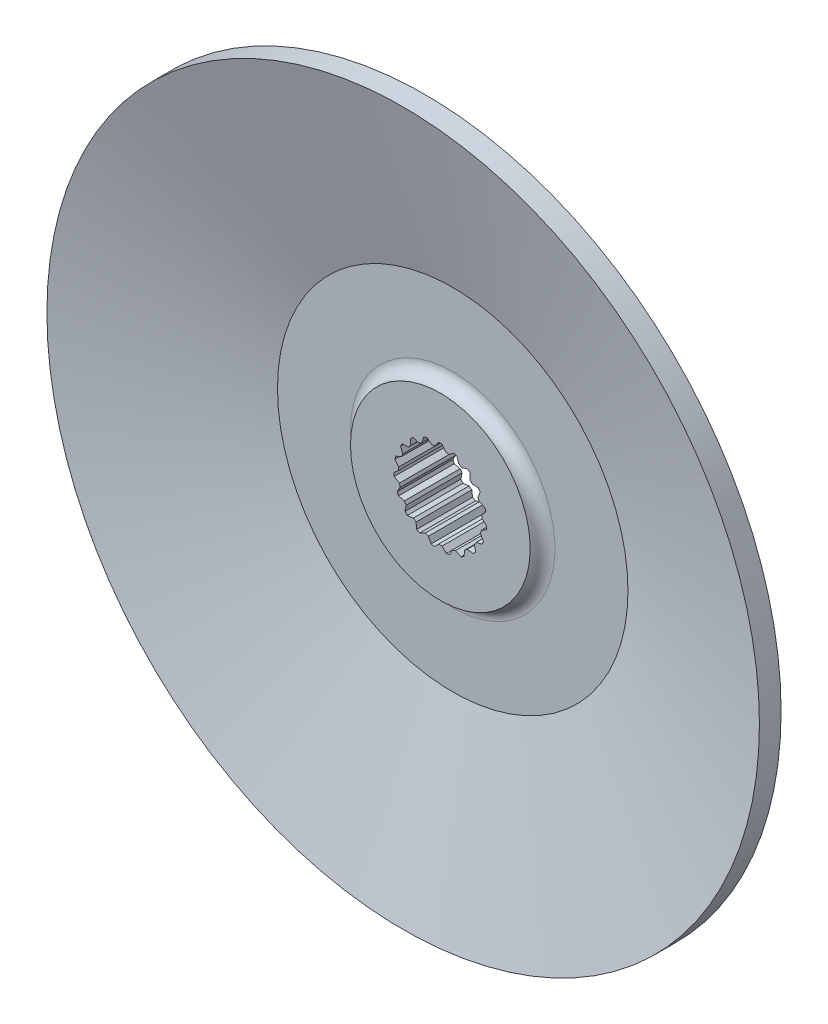
SolidWorks part; units mm, degrees
material "6061-T6 (SS)"
ref_plane "Front" through (0, 0, 0) normal (0, 0, 1) x (1, 0, 0)
ref_plane "Top" through (0, 0, 0) normal (0, 1, 0) x (1, 0, 0)
ref_plane "Right" through (0, 0, 0) normal (1, 0, 0) x (0, 0, -1)
sketch "Sketch1" plane through (0, 0, 0) normal (1, 0, 0) x (0, 0, -1)
  line L0 (0, 0) -> (-13885.9332, 0) construction
  line L1 (4.5, 6.75) -> (-4.5, 6.75)
  line L2 (4.5, 6.75) -> (4.5, 15.5)
  line L3 (4.5, 15.5) -> (-7, 57.5)
  line L4 (-7, 57.5) -> (-10.5, 57.5)
  line L5 (-10.5, 57.5) -> (-2.5, 28.2826)
  line L6 (-2.5, 28.2826) -> (-2.5, 16.5)
  line L7 (-4.5, 14.5) -> (-4.5, 6.75)
  arc A0 (-2.5, 16.5) -> (-4.5, 14.5) centre (-4.5, 16.5) cw
  point P5 (0, 6.75)
  dimension "D4" = 2
  dimension "D1" = 13.5
  dimension "D2" = 9
  dimension "D3" = 29
  dimension "D5" = 115
  dimension "D6" = 31
  dimension "D7" = 15
  dimension "D8" = 3.5
revolve "Revolve1" add sketch "Sketch1" angle 360 about L0
sketch "Sketch5" plane through (0, 0, 4.5) normal (0, 0, 1) x (1, 0, 0)
  line L0 (-0.2721, 7.4951) -> (-0.8417, 6.6973)
  line L1 (0.2721, 7.4951) -> (0.8417, 6.6973)
  line L2 (2.1763, 7.1773) -> (1.3785, 6.6077)
  line L3 (2.691, 7.0006) -> (2.9707, 6.0611)
  line L4 (4.3888, 6.0818) -> (3.4494, 5.8021)
  line L5 (4.8183, 5.7475) -> (4.7778, 4.7681)
  line L6 (6.1258, 4.3272) -> (5.1464, 4.3677)
  line L7 (6.4235, 3.8716) -> (6.0671, 2.9584)
  line L8 (7.1989, 2.1037) -> (6.2858, 2.46)
  line L9 (7.3325, 1.5761) -> (6.699, 0.8281)
  line L10 (7.4919, -0.3477) -> (6.7439, 0.2858)
  line L11 (7.447, -0.8901) -> (6.6049, -1.3919)
  line L12 (6.9731, -2.7615) -> (6.4713, -1.9195)
  line L13 (6.7545, -3.2599) -> (5.7951, -3.4611)
  line L14 (5.6986, -4.8761) -> (5.4974, -3.9167)
  line L15 (5.33, -5.2765) -> (4.3573, -5.1552)
  line L16 (3.8066, -6.4622) -> (3.9278, -5.4895)
  line L17 (3.3279, -6.7212) -> (2.4473, -6.2907)
  line L18 (1.5021, -7.348) -> (1.9326, -6.4674)
  line L19 (0.9652, -7.4376) -> (0.2721, -6.7445)
  line L20 (-0.9652, -7.4376) -> (-0.2721, -6.7445)
  line L21 (-1.5021, -7.348) -> (-1.9326, -6.4674)
  line L22 (-3.3279, -6.7212) -> (-2.4473, -6.2907)
  line L23 (-3.8066, -6.4622) -> (-3.9278, -5.4895)
  line L24 (-5.33, -5.2765) -> (-4.3573, -5.1552)
  line L25 (-5.6986, -4.8761) -> (-5.4974, -3.9167)
  line L26 (-6.7545, -3.2599) -> (-5.7951, -3.4611)
  line L27 (-6.9731, -2.7615) -> (-6.4713, -1.9195)
  line L28 (-7.447, -0.8901) -> (-6.6049, -1.3919)
  line L29 (-7.4919, -0.3477) -> (-6.7439, 0.2858)
  line L30 (-7.3325, 1.5761) -> (-6.699, 0.8281)
  line L31 (-7.1989, 2.1037) -> (-6.2858, 2.46)
  line L32 (-6.4235, 3.8716) -> (-6.0671, 2.9584)
  line L33 (-6.1258, 4.3272) -> (-5.1464, 4.3677)
  line L34 (-4.8183, 5.7475) -> (-4.7778, 4.7681)
  line L35 (-4.3888, 6.0818) -> (-3.4494, 5.8021)
  line L36 (-2.691, 7.0006) -> (-2.9707, 6.0611)
  line L37 (-2.1763, 7.1773) -> (-1.3785, 6.6077)
  line L38 (-2.1763, 7.1773) -> (-0.2721, 7.4951) construction
  line L39 (-0.8417, 6.6973) -> (-1.3785, 6.6077) construction
  line L40 (-2.1763, 7.1773) -> (-2.691, 7.0006) construction
  line L41 (-1.3785, 6.6077) -> (-2.9707, 6.0611) construction
  arc A0 (0.2721, 7.4951) -> (-0.2721, 7.4951) centre (0, 0) ccw
  circle A1 centre (0, 0) radius 6.75 construction
  arc A2 (0.8417, 6.6973) -> (-0.8417, 6.6973) centre (0, 0) ccw
  arc A3 (2.691, 7.0006) -> (2.1763, 7.1773) centre (0, 0) ccw
  arc A4 (2.9707, 6.0611) -> (1.3785, 6.6077) centre (0, 0) ccw
  arc A5 (4.8183, 5.7475) -> (4.3888, 6.0818) centre (0, 0) ccw
  arc A6 (4.7778, 4.7681) -> (3.4494, 5.8021) centre (0, 0) ccw
  arc A7 (6.4235, 3.8716) -> (6.1258, 4.3272) centre (0, 0) ccw
  arc A8 (6.0671, 2.9584) -> (5.1464, 4.3677) centre (0, 0) ccw
  arc A9 (7.3325, 1.5761) -> (7.1989, 2.1037) centre (0, 0) ccw
  arc A10 (6.699, 0.8281) -> (6.2858, 2.46) centre (0, 0) ccw
  arc A11 (7.447, -0.8901) -> (7.4919, -0.3477) centre (0, 0) ccw
  arc A12 (6.6049, -1.3919) -> (6.7439, 0.2858) centre (0, 0) ccw
  arc A13 (6.7545, -3.2599) -> (6.9731, -2.7615) centre (0, 0) ccw
  arc A14 (5.7951, -3.4611) -> (6.4713, -1.9195) centre (0, 0) ccw
  arc A15 (5.33, -5.2765) -> (5.6986, -4.8761) centre (0, 0) ccw
  arc A16 (4.3573, -5.1552) -> (5.4974, -3.9167) centre (0, 0) ccw
  arc A17 (3.3279, -6.7212) -> (3.8066, -6.4622) centre (0, 0) ccw
  arc A18 (2.4473, -6.2907) -> (3.9278, -5.4895) centre (0, 0) ccw
  arc A19 (0.9652, -7.4376) -> (1.5021, -7.348) centre (0, 0) ccw
  arc A20 (0.2721, -6.7445) -> (1.9326, -6.4674) centre (0, 0) ccw
  arc A21 (-1.5021, -7.348) -> (-0.9652, -7.4376) centre (0, 0) ccw
  arc A22 (-1.9326, -6.4674) -> (-0.2721, -6.7445) centre (0, 0) ccw
  arc A23 (-3.8066, -6.4622) -> (-3.3279, -6.7212) centre (0, 0) ccw
  arc A24 (-3.9278, -5.4895) -> (-2.4473, -6.2907) centre (0, 0) ccw
  arc A25 (-5.6986, -4.8761) -> (-5.33, -5.2765) centre (0, 0) ccw
  arc A26 (-5.4974, -3.9167) -> (-4.3573, -5.1552) centre (0, 0) ccw
  arc A27 (-6.9731, -2.7615) -> (-6.7545, -3.2599) centre (0, 0) ccw
  arc A28 (-6.4713, -1.9195) -> (-5.7951, -3.4611) centre (0, 0) ccw
  arc A29 (-7.4919, -0.3477) -> (-7.447, -0.8901) centre (0, 0) ccw
  arc A30 (-6.7439, 0.2858) -> (-6.6049, -1.3919) centre (0, 0) ccw
  arc A31 (-7.1989, 2.1037) -> (-7.3325, 1.5761) centre (0, 0) ccw
  arc A32 (-6.2858, 2.46) -> (-6.699, 0.8281) centre (0, 0) ccw
  arc A33 (-6.1258, 4.3272) -> (-6.4235, 3.8716) centre (0, 0) ccw
  arc A34 (-5.1464, 4.3677) -> (-6.0671, 2.9584) centre (0, 0) ccw
  arc A35 (-4.3888, 6.0818) -> (-4.8183, 5.7475) centre (0, 0) ccw
  arc A36 (-3.4494, 5.8021) -> (-4.7778, 4.7681) centre (0, 0) ccw
  arc A37 (-2.1763, 7.1773) -> (-2.691, 7.0006) centre (0, 0) ccw
  arc A38 (-1.3785, 6.6077) -> (-2.9707, 6.0611) centre (0, 0) ccw
  point P5 (0, 6.75)
  point P7 (0, 7.5)
  point P84 (0, 0)
  dimension "D1" = 15
  dimension "D2" = 19
extrude "Cut-Extrude2" cut sketch "Sketch5" against normal through all
